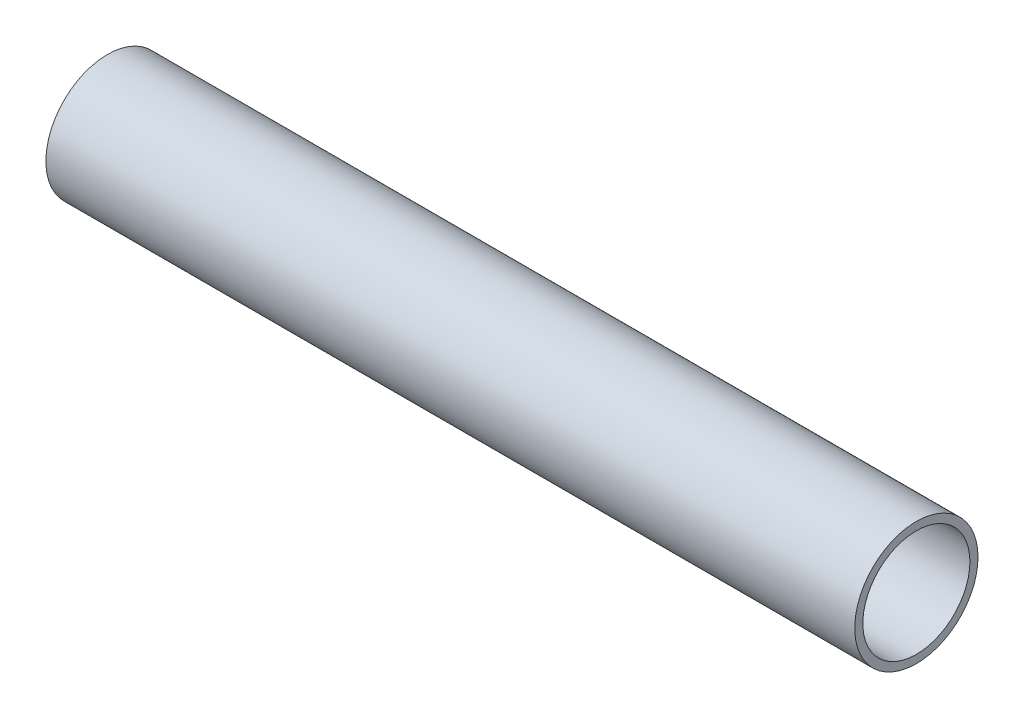
SolidWorks part; units mm, degrees
ref_plane "Front Plane" through (0, 0, 0) normal (1, 0, 0) x (0, 1, 0)
ref_plane "Top Plane" through (0, 0, 0) normal (0, 0, 1) x (0, 1, 0)
ref_plane "Right Plane" through (0, 0, 0) normal (0, 1, 0) x (-1, 0, 0)
sketch "Sketch1" plane through (0, 0, 0) normal (1, 0, 0) x (0, 1, 0)
  circle A0 centre (0, 0) radius 76.2
  circle A1 centre (0, 0) radius 66.2
  dimension "D1" = 152.4
  dimension "D2" = 10
extrude "Boss-Extrude1" add sketch "Sketch1" along normal blind 1000
